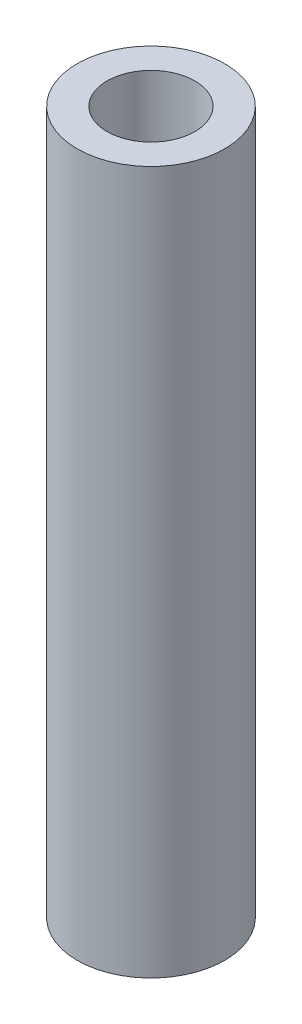
SolidWorks part; units mm, degrees
ref_plane "Front Plane" through (0, 0, 0) normal (0, 0, 1) x (1, 0, 0)
ref_plane "Top Plane" through (0, 0, 0) normal (0, 1, 0) x (1, 0, 0)
ref_plane "Right Plane" through (0, 0, 0) normal (1, 0, 0) x (0, 0, -1)
sketch "Sketch3" plane through (0, 0, 0) normal (0, 1, 0) x (1, 0, 0)
  circle A0 centre (0, 0) radius 6.35
  circle A1 centre (0, 0) radius 10.668
extrude "Boss-Extrude1" add sketch "Sketch3" along normal blind 101.6
